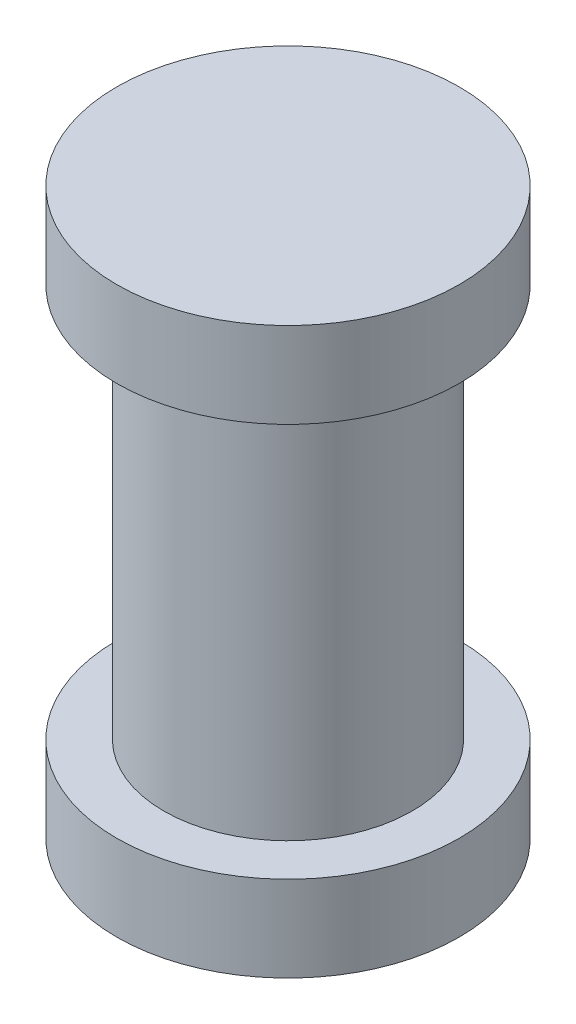
SolidWorks part; units mm, degrees
material "Plain Carbon Steel"
ref_plane "Front Plane" through (0, 0, 0) normal (0, 0, 1) x (1, 0, 0)
ref_plane "Top Plane" through (0, 0, 0) normal (0, 1, 0) x (1, 0, 0)
ref_plane "Right Plane" through (0, 0, 0) normal (1, 0, 0) x (0, 0, -1)
sketch "Sketch1" plane through (0, 0, 0) normal (0, 1, 0) x (1, 0, 0)
  circle A0 centre (0, 0) radius 1.45
  dimension "D1" = 2.9
extrude "MID BODY" add sketch "Sketch1" along normal mid plane 4.6
sketch "Sketch2" plane through (0, 2.3, 0) normal (0, 1, 0) x (1, 0, 0)
  circle A0 centre (0, 0) radius 2
  circle A1 centre (0, 0) radius 1.45 construction
  dimension "D1" = 4
extrude "TOP HEAD" add sketch "Sketch2" along normal blind 1
mirror "BOTTOM HEAD" about plane through (0, 0, 0) normal (0, 1, 0) of "TOP HEAD"
